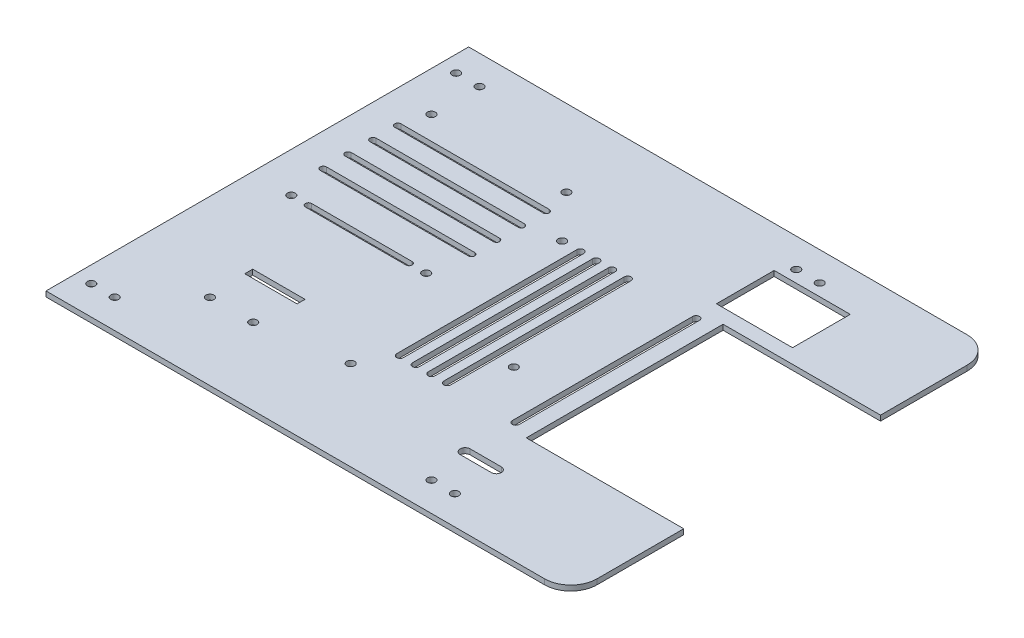
SolidWorks part; units mm, degrees
ref_plane "Front Plane" through (0, 0, 0) normal (0, 0, 1) x (1, 0, 0)
ref_plane "Top Plane" through (0, 0, 0) normal (0, 1, 0) x (1, 0, 0)
ref_plane "Right Plane" through (0, 0, 0) normal (1, 0, 0) x (0, 0, -1)
sketch "Sketch1" plane through (0, 0, 0) normal (0, 1, 0) x (1, 0, 0)
  line L0 (62.5, -37.5) -> (62.5, -80.53)
  line L1 (-137.5, 80.53) -> (62.5, 80.53)
  line L2 (-137.5, 80.53) -> (-137.5, -80.53)
  line L3 (-137.5, -80.53) -> (62.5, -80.53)
  line L4 (62.5, 80.53) -> (62.5, 37.5)
  line L5 (0, 0) -> (2.5, -3) construction
  line L6 (0, 0) -> (2.5, 3) construction
  line L7 (2.5, 37.5) -> (62.5, 37.5)
  line L8 (2.5, 37.5) -> (2.5, -37.5)
  line L9 (2.5, -37.5) -> (62.5, -37.5)
  point P0 (0, 0)
  point P5 (32.5, 0)
  dimension "D1" = 161.06
  dimension "D2" = 200
  dimension "D3" = 75
  dimension "D4" = 60
  dimension "D5" = 0
  dimension "D6" = 32.5
  dimension "D7" = 80.53
  dimension "D8" = 37.5
extrude "Boss-Extrude1" add sketch "Sketch1" along normal blind 2
sketch "Sketch2" plane through (0, 2, 0) normal (0, 1, 0) x (1, 0, 0)
  line L0 (26.8587, 0) -> (-74.6271, 0) construction
  line L1 (-4.5625, 34.283) -> (-4.5625, -34.4223) construction
  line L2 (-3.2652, 34.283) -> (-3.2652, -34.4223)
  line L3 (-5.8598, 34.283) -> (-5.8598, -34.4223)
  line L4 (-30.6709, 34.283) -> (-30.6709, -34.4223) construction
  line L5 (-29.3736, 34.283) -> (-29.3736, -34.4223)
  line L6 (-31.9682, 34.283) -> (-31.9682, -34.4223)
  line L7 (-36.6709, 34.283) -> (-36.6709, -34.4223) construction
  line L8 (-35.3736, 34.283) -> (-35.3736, -34.4223)
  line L9 (-37.9682, 34.283) -> (-37.9682, -34.4223)
  line L10 (-42.6709, 34.283) -> (-42.6709, -34.4223) construction
  line L11 (-41.3736, 34.283) -> (-41.3736, -34.4223)
  line L12 (-43.9682, 34.283) -> (-43.9682, -34.4223)
  line L13 (-48.6709, 34.283) -> (-48.6709, -34.4223) construction
  line L14 (-47.3736, 34.283) -> (-47.3736, -34.4223)
  line L15 (-49.9682, 34.283) -> (-49.9682, -34.4223)
  line L16 (-115.7691, -2.2272) -> (-77.4568, -2.2272) construction
  line L17 (-115.7691, -1.0564) -> (-77.4568, -1.0564)
  line L18 (-85.3754, -36.9699) -> (-105.2959, -36.9699)
  line L19 (-85.3754, -36.9699) -> (-85.3754, -33.9516)
  line L20 (-85.3754, -33.9516) -> (-105.2959, -33.9516)
  line L21 (-105.2959, -36.9699) -> (-105.2959, -33.9516)
  line L22 (-68.5211, 41.098) -> (-125.0341, 41.098) construction
  line L23 (-68.5211, 39.9249) -> (-125.0341, 39.9249)
  line L24 (-68.5211, 42.2712) -> (-125.0341, 42.2712)
  line L25 (-68.5211, 31.6224) -> (-125.0341, 31.6224) construction
  line L26 (-68.5211, 30.4493) -> (-125.0341, 30.4493)
  line L27 (-68.5211, 32.7955) -> (-125.0341, 32.7955)
  line L28 (-68.5211, 22.1468) -> (-125.0341, 22.1468) construction
  line L29 (-68.5211, 20.9736) -> (-125.0341, 20.9736)
  line L30 (-68.5211, 23.3199) -> (-125.0341, 23.3199)
  line L31 (-68.5211, 12.6712) -> (-125.0341, 12.6712) construction
  line L32 (-68.5211, 11.498) -> (-125.0341, 11.498)
  line L33 (-68.5211, 13.8443) -> (-125.0341, 13.8443)
  line L34 (62.5, 80.53) -> (-137.5, 80.53) construction
  line L35 (-5.5167, 64.9842) -> (23.4833, 64.9842)
  line L36 (-5.5167, 64.9842) -> (-5.5167, 42.9842)
  line L37 (7.3032, -53.7238) -> (-4.5625, -53.7238) construction
  line L38 (7.3032, -51.8243) -> (-4.5625, -51.8243)
  line L39 (7.3032, -55.6233) -> (-4.5625, -55.6233)
  line L40 (-5.5167, 42.9842) -> (23.4833, 42.9842)
  line L41 (23.4833, 64.9842) -> (23.4833, 42.9842)
  line L42 (-5.5167, 64.9842) -> (23.4833, 42.9842) construction
  line L43 (-5.5167, 42.9842) -> (23.4833, 64.9842) construction
  line L44 (-85.3754, -36.9699) -> (-105.2959, -33.9516) construction
  line L45 (-115.7691, -3.3979) -> (-77.4568, -3.3979)
  line L50 (-85.3754, -33.9516) -> (-105.2959, -36.9699) construction
  circle A0 centre (-131.2565, -69.5158) radius 1.5
  circle A1 centre (7.3032, -69.5158) radius 1.5
  circle A2 centre (-131.2565, 69.5158) radius 1.5
  circle A3 centre (7.3032, 69.5158) radius 1.5
  circle A4 centre (-122.3325, -69.5158) radius 1.5
  circle A5 centre (-1.6235, -69.5158) radius 1.5
  circle A6 centre (-1.6235, 69.5158) radius 1.5
  circle A7 centre (-122.3325, 69.5158) radius 1.5
  circle A8 centre (-23.2386, -16.5121) radius 1.5
  circle A9 centre (-55.491, -46.4371) radius 1.5
  circle A10 centre (-55.6188, 34.283) radius 1.5
  circle A11 centre (-70.9125, 51.1928) radius 1.5
  circle A12 centre (-122.3325, 51.1928) radius 1.5
  circle A13 centre (-122.3325, -2.2272) radius 1.5
  circle A14 centre (-70.9125, -2.2272) radius 1.5
  circle A15 centre (-104.1446, -51.3927) radius 1.5
  circle A16 centre (-87.6732, -51.3927) radius 1.5
  arc A17 (-3.2652, 34.283) -> (-5.8598, 34.283) centre (-4.5625, 34.283) ccw
  arc A18 (-5.8598, -34.4223) -> (-3.2652, -34.4223) centre (-4.5625, -34.4223) ccw
  arc A19 (-29.3736, 34.283) -> (-31.9682, 34.283) centre (-30.6709, 34.283) ccw
  arc A20 (-31.9682, -34.4223) -> (-29.3736, -34.4223) centre (-30.6709, -34.4223) ccw
  arc A21 (-35.3736, 34.283) -> (-37.9682, 34.283) centre (-36.6709, 34.283) ccw
  arc A22 (-37.9682, -34.4223) -> (-35.3736, -34.4223) centre (-36.6709, -34.4223) ccw
  arc A23 (-41.3736, 34.283) -> (-43.9682, 34.283) centre (-42.6709, 34.283) ccw
  arc A24 (-43.9682, -34.4223) -> (-41.3736, -34.4223) centre (-42.6709, -34.4223) ccw
  arc A25 (-47.3736, 34.283) -> (-49.9682, 34.283) centre (-48.6709, 34.283) ccw
  arc A26 (-49.9682, -34.4223) -> (-47.3736, -34.4223) centre (-48.6709, -34.4223) ccw
  arc A27 (-115.7691, -1.0564) -> (-115.7691, -3.3979) centre (-115.7691, -2.2272) ccw
  arc A28 (-77.4568, -3.3979) -> (-77.4568, -1.0564) centre (-77.4568, -2.2272) ccw
  arc A31 (-68.5211, 39.9249) -> (-68.5211, 42.2712) centre (-68.5211, 41.098) ccw
  arc A32 (-125.0341, 42.2712) -> (-125.0341, 39.9249) centre (-125.0341, 41.098) ccw
  arc A33 (-68.5211, 30.4493) -> (-68.5211, 32.7955) centre (-68.5211, 31.6224) ccw
  arc A34 (-125.0341, 32.7955) -> (-125.0341, 30.4493) centre (-125.0341, 31.6224) ccw
  arc A35 (-68.5211, 20.9736) -> (-68.5211, 23.3199) centre (-68.5211, 22.1468) ccw
  arc A36 (-125.0341, 23.3199) -> (-125.0341, 20.9736) centre (-125.0341, 22.1468) ccw
  arc A37 (-68.5211, 11.498) -> (-68.5211, 13.8443) centre (-68.5211, 12.6712) ccw
  arc A38 (-125.0341, 13.8443) -> (-125.0341, 11.498) centre (-125.0341, 12.6712) ccw
  arc A41 (7.3032, -51.8243) -> (7.3032, -55.6233) centre (7.3032, -53.7238) cw
  arc A42 (-4.5625, -55.6233) -> (-4.5625, -51.8243) centre (-4.5625, -53.7238) cw
  point P43 (-4.5625, -0.0696)
  point P48 (-30.6709, -0.0696)
  point P57 (-36.6709, -0.0696)
  point P64 (-42.6709, -0.0696)
  point P71 (-48.6709, -0.0696)
  point P82 (-95.3357, -35.4607)
  point P83 (-96.6129, -2.2272)
  point P90 (-96.7776, 41.098)
  point P97 (8.9833, 53.9842)
  point P98 (-96.7776, 31.6224)
  point P105 (-96.7776, 22.1468)
  point P112 (-96.7776, 12.6712)
  point P127 (1.3703, -53.7238)
  dimension "D1" = 4
  dimension "D2" = 4
  dimension "D3" = 22
  dimension "D4" = 29
  dimension "D5" = 15.5458
  dimension "D6" = 3.0183
  dimension "D7" = 19.9205
extrude "Cut-Extrude1" cut sketch "Sketch2" against normal up to surface (2 mm away) up to face at (-2.5, 0, 0)
fillet "Fillet1" radius 10 2 edges at (62.5, 1, -80.53) (62.5, 1, 80.53)
